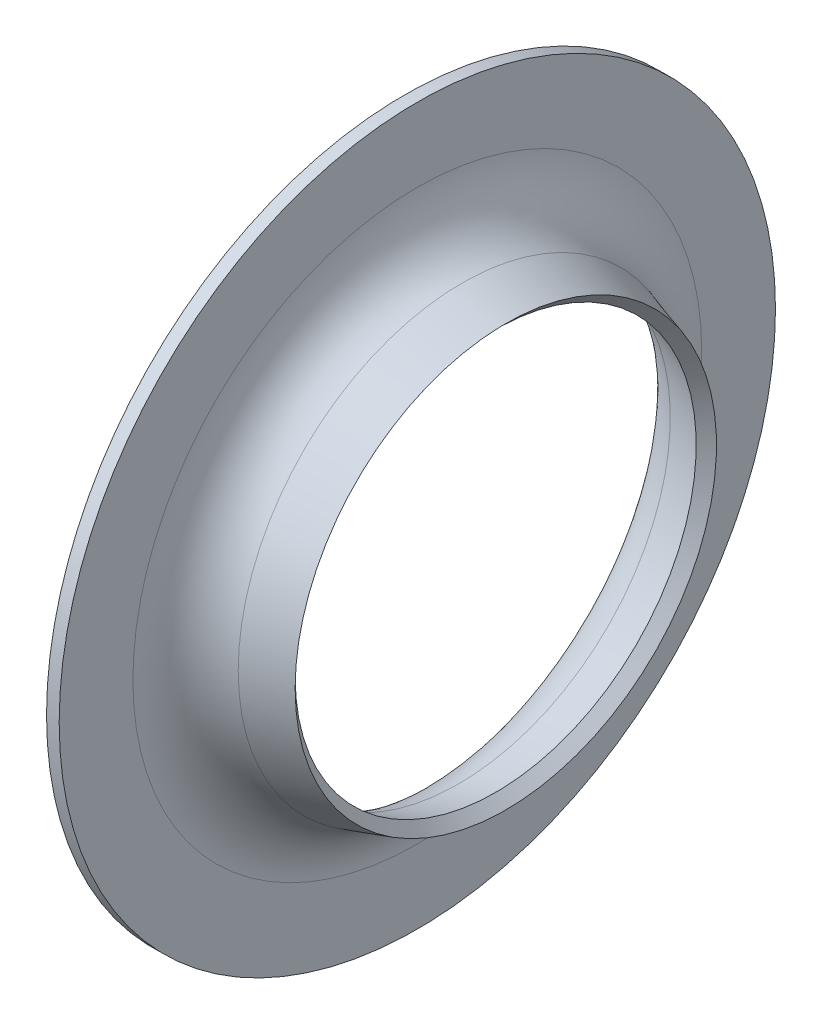
SolidWorks part; units mm, degrees
ref_plane "前视基准面" through (0, 0, 0) normal (0, 0, 1) x (1, 0, 0)
ref_plane "上视基准面" through (0, 0, 0) normal (0, 1, 0) x (1, 0, 0)
ref_plane "右视基准面" through (0, 0, 0) normal (1, 0, 0) x (0, 0, -1)
sketch "草图1" plane through (0, 0, 0) normal (0, 0, 1) x (1, 0, 0)
  line L0 (-48.7456, 0) -> (26.441, 0) construction
  line L1 (0, 37.122) -> (0, -32.0957) construction
  line L2 (-4.2, 17) -> (-4.2, 13.5)
  line L3 (-2.0721, 10.6296) -> (0, 10)
  line L4 (-4.8, 17) -> (-4.8, 13.5)
  line L5 (-2.2465, 10.0555) -> (-0.481, 9.519)
  line L6 (-4.8, 17) -> (-4.2, 17)
  line L7 (0, 10) -> (-0.481, 9.519)
  line L9 (-2.2465, 10.0555) -> (-0.1744, 9.4259) construction
  arc A0 (-2.0721, 10.6296) -> (-4.2, 13.5) centre (-1.2, 13.5) cw
  arc A1 (-2.2465, 10.0555) -> (-4.8, 13.5) centre (-1.2, 13.5) cw
  dimension "D5" = 3
  dimension "D1" = 20
  dimension "D2" = 4.2
  dimension "D3" = 34
  dimension "D4" = 27
  dimension "D6" = 2.1656
  dimension "D8" = 45
  dimension "D7" = 0.6
revolve "旋转1" add sketch "草图1" angle 360 about L0
